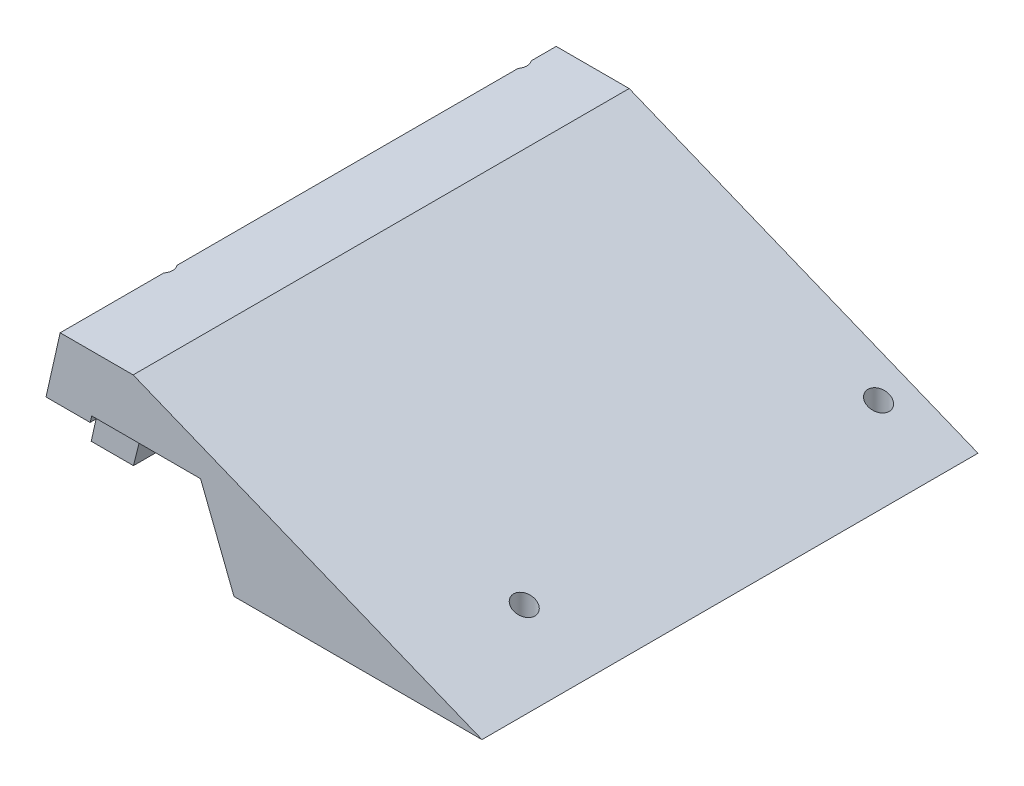
SolidWorks part; units mm, degrees
ref_plane "Front" through (0, 0, 0) normal (0, 0, 1) x (1, 0, 0)
ref_plane "Top" through (0, 0, 0) normal (0, 1, 0) x (1, 0, 0)
ref_plane "Right" through (0, 0, 0) normal (1, 0, 0) x (0, 0, -1)
sketch "草图1" plane through (0, 0, 0) normal (0, 0, 1) x (1, 0, 0)
  line L0 (5.3689, 0) -> (10.7378, 0)
  line L1 (63, 0) -> (18.6962, 17.9645)
  line L2 (18.6962, 17.9645) -> (9.4265, 17.9645)
  line L3 (13.4333, 10.8252) -> (10.7378, 0)
  line L5 (13.4333, 10.8252) -> (27.262, 10.8252)
  line L6 (27.262, 10.8252) -> (31.5, 0)
  line L7 (31.5, 0) -> (63, 0)
  line L8 (9.4265, 17.9645) -> (5.3689, 0)
extrude "凸台-拉伸1" add sketch "草图1" along normal blind 63
sketch "草图2" plane through (0, 0, 0) normal (0, 0, -1) x (-1, 0, 0)
  line L0 (-31.5, 0) -> (-27.262, 10.8252)
  line L1 (-27.262, 10.8252) -> (-13.4333, 10.8252)
  line L2 (-13.4333, 10.8252) -> (-27.262, 10.8252) construction
  line L3 (-13.4333, 10.8252) -> (-10.7378, 0)
  line L4 (-10.7378, 0) -> (-31.5, 0)
extrude "凸台-拉伸2" add sketch "草图2" against normal blind 6
sketch "草图3" plane through (0, 0, 0) normal (1, 0, 0) x (0, 0, -1)
  line L0 (-63, 0) -> (-63, 10)
  line L1 (-63, 0) -> (-63, 17.9645) construction
  line L2 (-63, 10) -> (-55, 10)
  line L3 (-55, 10) -> (-55, 0)
  line L4 (-63, 0) -> (0, 0) construction
  line L5 (-55, 0) -> (-63, 0)
extrude "切除-拉伸1" cut sketch "草图3" along normal blind 17
sketch "草图4" plane through (0, 0, 0) normal (0, -1, 0) x (1, 0, 0)
  circle A0 centre (8.3689, 49) radius 1.35
  circle A1 centre (54.3689, 49) radius 1.35
  circle A2 centre (54.3689, 4) radius 1.35
  circle A3 centre (8.3689, 4) radius 1.35
extrude "切除-拉伸2" cut sketch "草图4" against normal blind 34
